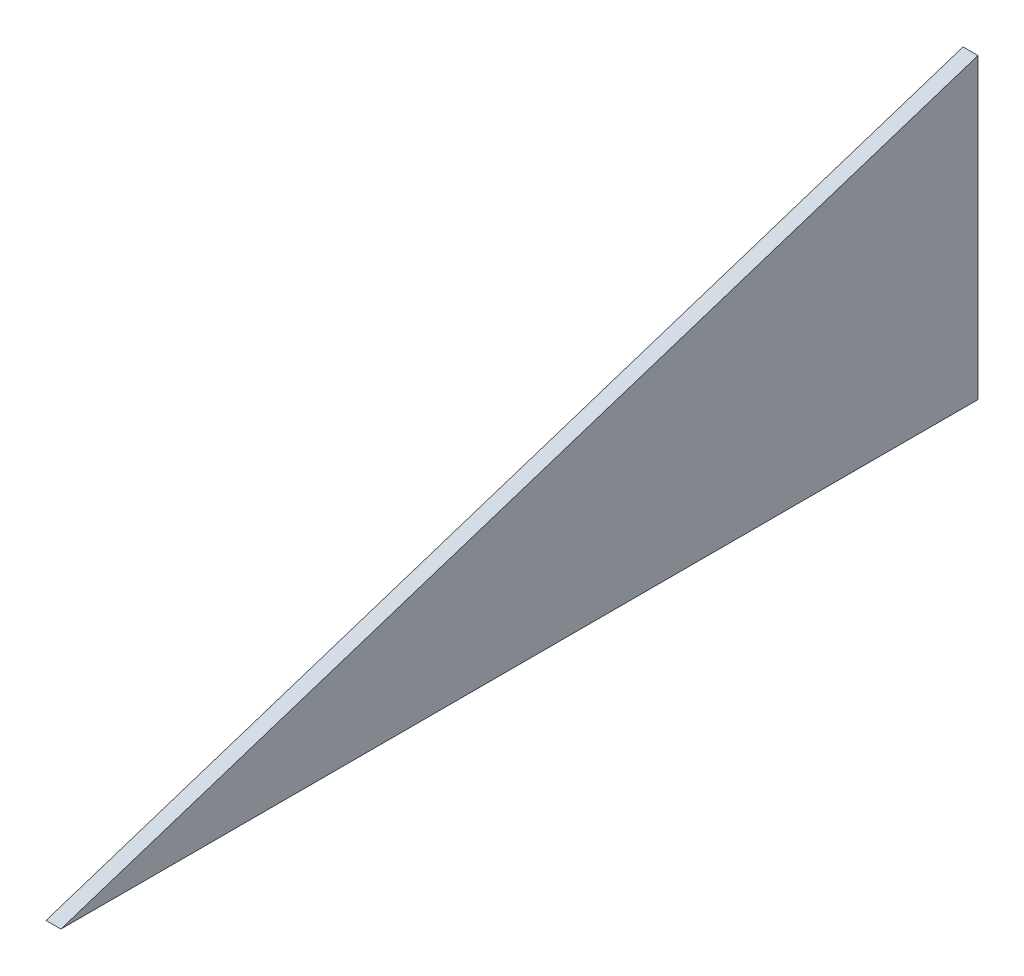
SolidWorks part; units mm, degrees
ref_plane "Front Plane" through (0, 0, 0) normal (0, 0, 1) x (1, 0, 0)
ref_plane "Top Plane" through (0, 0, 0) normal (0, 1, 0) x (1, 0, 0)
ref_plane "Right Plane" through (0, 0, 0) normal (1, 0, 0) x (0, 0, -1)
sketch "Sketch1" plane through (0, 0, 0) normal (1, 0, 0) x (0, 0, -1)
  line L0 (0, 0) -> (307.7684, 100)
  line L1 (307.7684, 100) -> (307.7684, 0)
  line L2 (307.7684, 0) -> (0, 0)
  dimension "D1" = 18
  dimension "D2" = 100
  dimension "D3" = 307.7684
  dimension "D4" = 323.6068
extrude "Boss-Extrude1" add sketch "Sketch1" along normal blind 5
